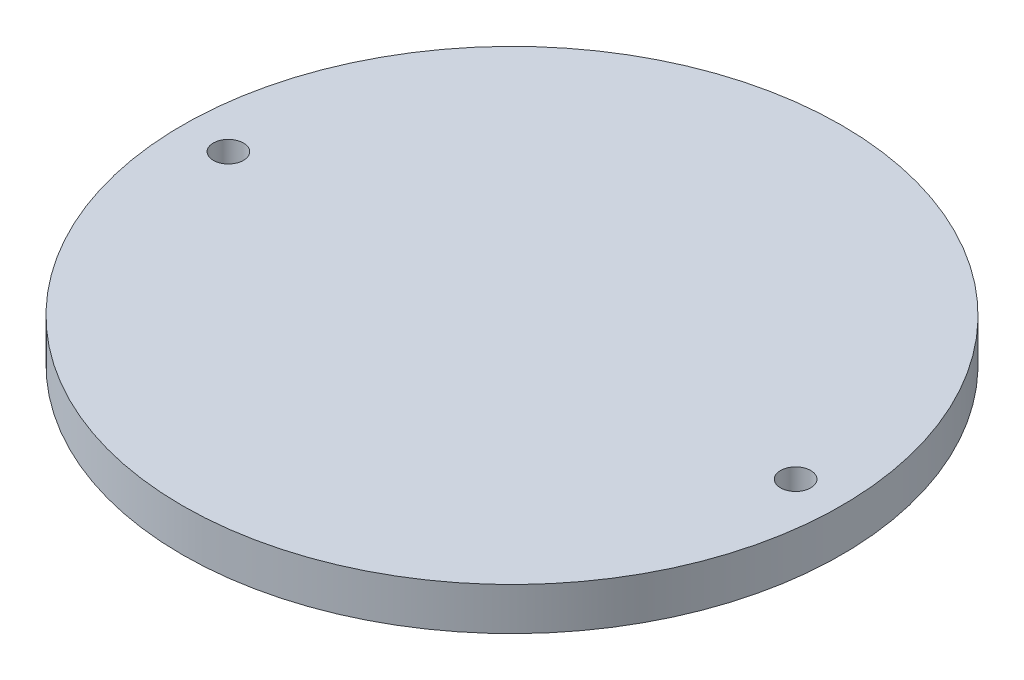
SolidWorks part; units mm, degrees
ref_plane "Front Plane" through (0, 0, 0) normal (0, 0, 1) x (1, 0, 0)
ref_plane "Top Plane" through (0, 0, 0) normal (0, 1, 0) x (1, 0, 0)
ref_plane "Right Plane" through (0, 0, 0) normal (1, 0, 0) x (0, 0, -1)
sketch "Sketch1" plane through (0, 0, 0) normal (0, 1, 0) x (1, 0, 0)
  circle A0 centre (0, 0) radius 73.787
  dimension "D1" = 147.574
extrude "Boss-Extrude1" add sketch "Sketch1" along normal blind 9.525 contours A0
sketch "Sketch2" plane through (0, 9.525, 0) normal (0, 1, 0) x (1, 0, 0)
  line L0 (-63.5, 0) -> (63.5, 0) construction
  circle A0 centre (-63.5, 0) radius 3.3782
  circle A1 centre (63.5, 0) radius 3.3782
  point P4 (0, 0)
  dimension "D1" = 6.7564
  dimension "D2" = 63.5
extrude "Cut-Extrude1" cut sketch "Sketch2" against normal through all
